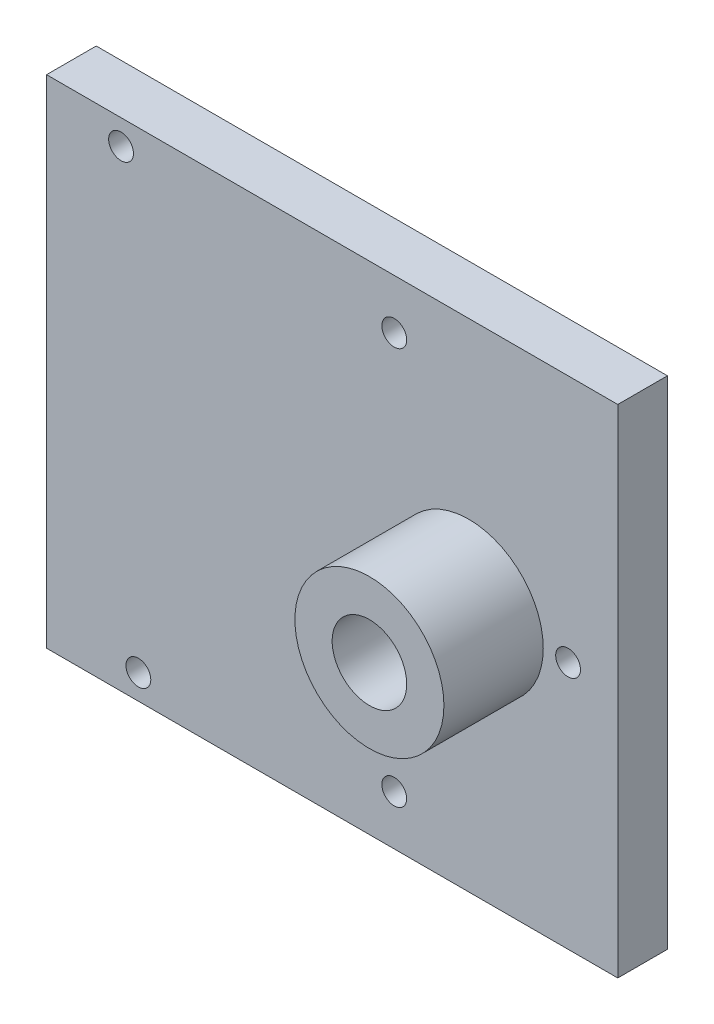
SolidWorks part; units mm, degrees
ref_plane "前视基准面" through (0, 0, 0) normal (0, 0, 1) x (1, 0, 0)
ref_plane "上视基准面" through (0, 0, 0) normal (0, 1, 0) x (1, 0, 0)
ref_plane "右视基准面" through (0, 0, 0) normal (1, 0, 0) x (0, 0, -1)
sketch "草图1" plane through (0, 0, 0) normal (0, 0, 1) x (1, 0, 0)
  line L1 (11.5, -10) -> (-11.5, -10)
  line L2 (11.5, -10) -> (11.5, 10)
  line L3 (11.5, 10) -> (-11.5, 10)
  line L4 (-11.5, -10) -> (-11.5, 10)
  line L5 (11.5, -10) -> (-11.5, 10) construction
  line L6 (11.5, 10) -> (-11.5, -10) construction
  circle A0 centre (-8.5, 9) radius 0.5
  circle A1 centre (-7.803, -9) radius 0.5
  circle A2 centre (9.5, 0) radius 0.5
  circle A3 centre (2.5, 8) radius 0.5
  circle A4 centre (2.5, -8) radius 0.5
  circle A5 centre (5.5, 0) radius 1.5
  point P0 (0, 0)
  dimension "D3" = 1
  dimension "D4" = 1
  dimension "D5" = 1
  dimension "D6" = 1
  dimension "D7" = 1
  dimension "D16" = 3
  dimension "D1" = 23
  dimension "D2" = 20
  dimension "D8" = 2
  dimension "D9" = 2
  dimension "D10" = 1
  dimension "D11" = 1
  dimension "D12" = 20
  dimension "D13" = 9
  dimension "D14" = 9
  dimension "D15" = 2
  dimension "D17" = 6
extrude "凸台-拉伸1" add sketch "草图1" along normal blind 2
sketch "草图2" plane through (0, 0, 2) normal (0, 0, 1) x (1, 0, 0)
  circle A0 centre (5.5, 0) radius 3
  circle A1 centre (5.5, 0) radius 1.5
  dimension "D1" = 6
extrude "凸台-拉伸2" add sketch "草图2" along normal blind 4
